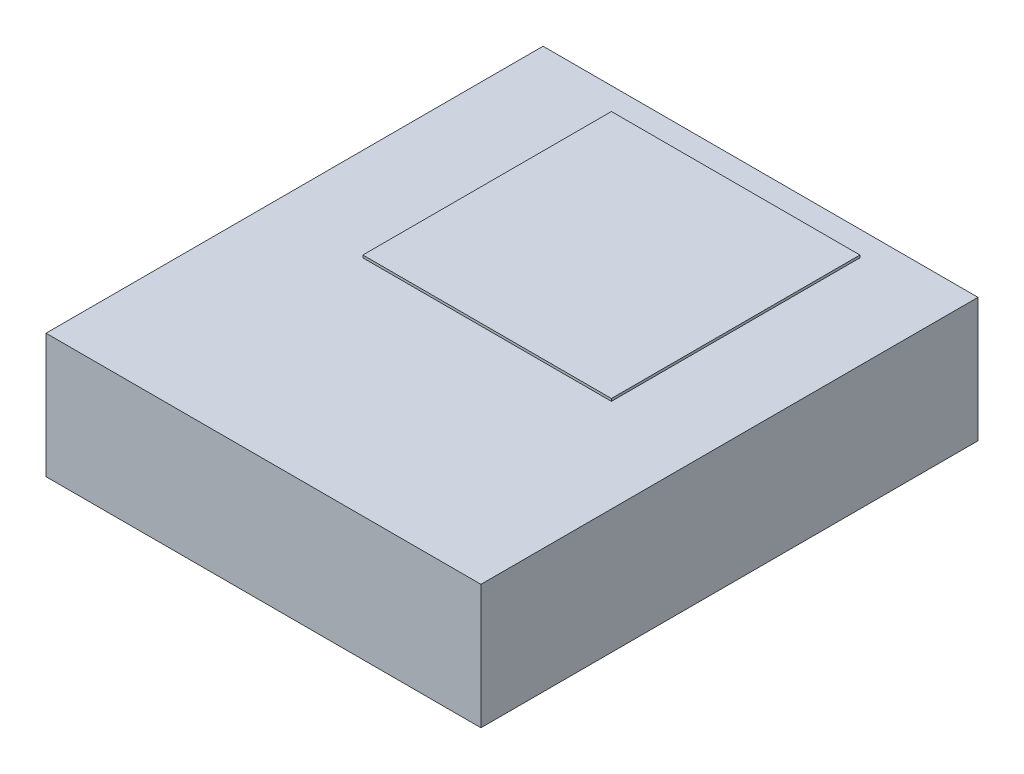
SolidWorks part; units mm, degrees
ref_plane "Piano frontale" through (0, 0, 0) normal (0, 0, 1) x (1, 0, 0)
ref_plane "Piano superiore" through (0, 0, 0) normal (0, 1, 0) x (1, 0, 0)
ref_plane "Piano destro" through (0, 0, 0) normal (1, 0, 0) x (0, 0, -1)
sketch "Schizzo1" plane through (0, 0, 0) normal (0, 1, 0) x (1, 0, 0)
  line L1 (-13.539, -5.5819) -> (-11.789, -5.5819)
  line L2 (-13.539, -5.5819) -> (-13.539, -7.5819)
  line L3 (-13.539, -7.5819) -> (-11.789, -7.5819)
  line L4 (-11.789, -5.5819) -> (-11.789, -7.5819)
  dimension "D1" = 2
  dimension "D2" = 1.75
extrude "Estrusione-Estrusione1" add sketch "Schizzo1" along normal blind 0.5
sketch "Schizzo2" plane through (0, 0.5, 0) normal (0, 1, 0) x (1, 0, 0)
  line L0 (-11.789, -5.5819) -> (-13.539, -5.5819) construction
  line L1 (-13.164, -5.6819) -> (-12.164, -5.6819)
  line L2 (-13.164, -5.6819) -> (-13.164, -6.6819)
  line L3 (-13.164, -6.6819) -> (-12.164, -6.6819)
  line L4 (-12.164, -5.6819) -> (-12.164, -6.6819)
  line L5 (-13.539, -5.5819) -> (-13.539, -7.5819) construction
  dimension "D1" = 1
  dimension "D2" = 1
  dimension "D3" = 0.1
  dimension "D4" = 0.375
extrude "Estrusione-Estrusione2" add sketch "Schizzo2" along normal blind 0.01
